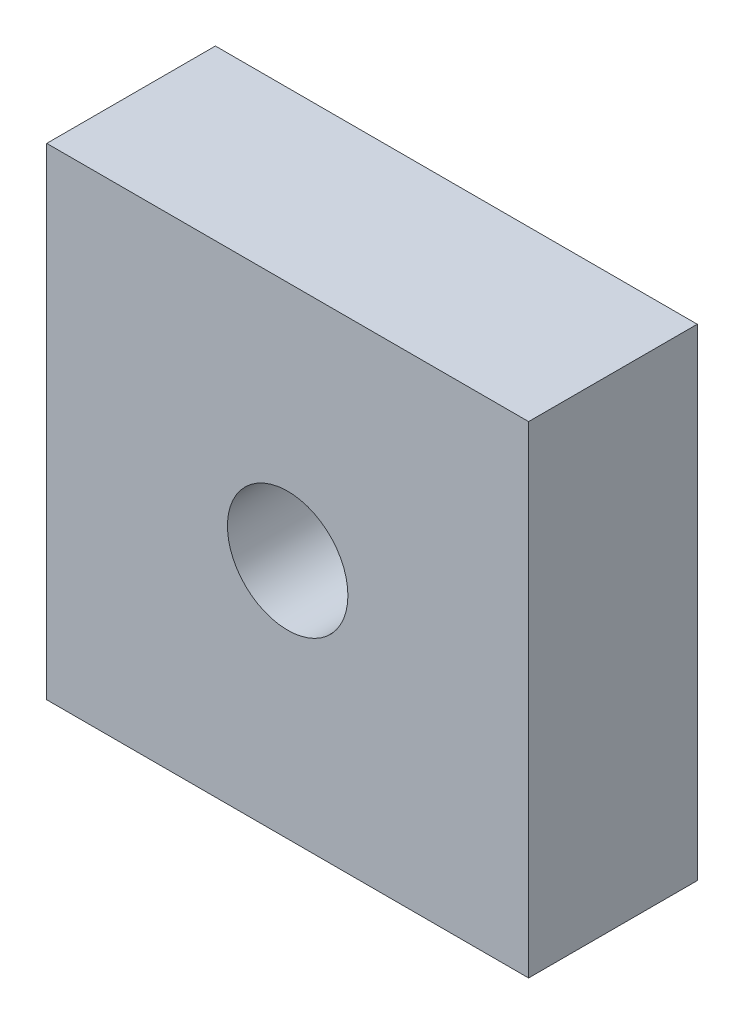
SolidWorks part; units mm, degrees
material "6063-T5"
ref_plane "Plano frontal" through (0, 0, 0) normal (0, 0, 1) x (1, 0, 0)
ref_plane "Plano superior" through (0, 0, 0) normal (0, 1, 0) x (1, 0, 0)
ref_plane "Plano direito" through (0, 0, 0) normal (1, 0, 0) x (0, 0, -1)
sketch "Esboço1" plane through (0, 0, 0) normal (0, 0, 1) x (1, 0, 0)
  line L1 (10, 10) -> (-10, 10)
  line L2 (10, 10) -> (10, -10)
  line L3 (10, -10) -> (-10, -10)
  line L4 (-10, 10) -> (-10, -10)
  line L5 (10, 10) -> (-10, -10) construction
  line L6 (10, -10) -> (-10, 10) construction
  circle A0 centre (0, 0) radius 2.5
  dimension "D1" = 5
  dimension "D2" = 20
  dimension "D3" = 20
extrude "Ressalto-extrusão1" add sketch "Esboço1" along normal blind 7
